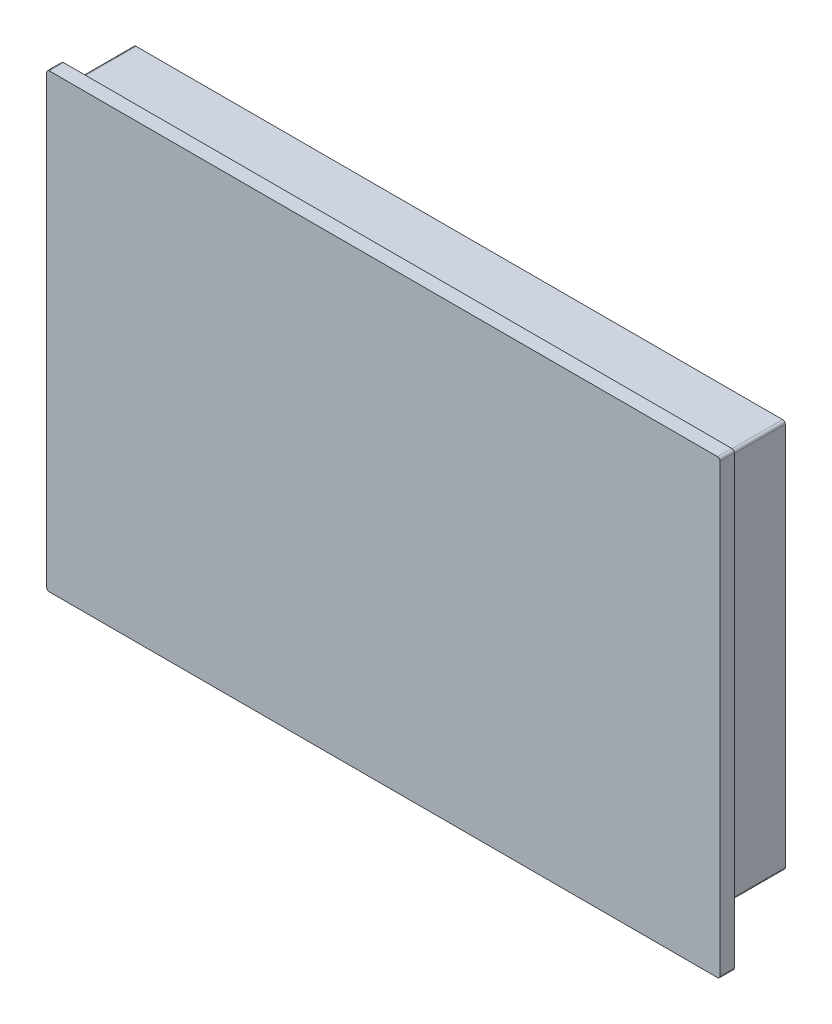
SolidWorks part; units mm, degrees
ref_plane "Front Plane" through (0, 0, 0) normal (0, 0, 1) x (1, 0, 0)
ref_plane "Top Plane" through (0, 0, 0) normal (0, 1, 0) x (1, 0, 0)
ref_plane "Right Plane" through (0, 0, 0) normal (1, 0, 0) x (0, 0, -1)
sketch "Sketch1" plane through (0, 0, 0) normal (0, 0, 1) x (1, 0, 0)
  line L1 (-63.8, 42.75) -> (63.8, 42.75)
  line L2 (-63.8, 42.75) -> (-63.8, -42.75)
  line L3 (-63.8, -42.75) -> (63.8, -42.75)
  line L4 (63.8, 42.75) -> (63.8, -42.75)
  line L5 (-63.8, 42.75) -> (63.8, -42.75) construction
  line L6 (-63.8, -42.75) -> (63.8, 42.75) construction
  point P0 (0, 0)
  dimension "D1" = 127.6
  dimension "D2" = 85.5
extrude "Boss-Extrude1" add sketch "Sketch1" along normal blind 14.4
sketch "Sketch2" plane through (0, 0, 0) normal (0, 0, -1) x (-1, 0, 0)
  line L1 (-61.75, 40.6) -> (61.75, 40.6)
  line L2 (-61.75, 40.6) -> (-61.75, -40.6)
  line L3 (-61.75, -40.6) -> (61.75, -40.6)
  line L4 (61.75, 40.6) -> (61.75, -40.6)
  line L5 (-61.75, 40.6) -> (61.75, -40.6) construction
  line L6 (-61.75, -40.6) -> (61.75, 40.6) construction
  line L16 (-63.8, 42.75) -> (-63.8, -42.75)
  line L17 (-63.8, -42.75) -> (63.8, -42.75)
  line L18 (63.8, -42.75) -> (63.8, 42.75)
  line L19 (63.8, 42.75) -> (-63.8, 42.75)
  line L20 (-63.8, 42.75) -> (-63.8, -42.75)
  line L21 (-63.8, -42.75) -> (63.8, -42.75)
  line L22 (63.8, -42.75) -> (63.8, 42.75)
  line L23 (63.8, 42.75) -> (-63.8, 42.75)
  point P2 (0, 0)
  dimension "D1" = 123.5
  dimension "D3" = 81.2
  dimension "D2" = 0
extrude "Cut-Extrude1" cut sketch "Sketch2" against normal blind 11.7
fillet "Fillet1" radius 0.5 8 edges at (63.8, 42.75, 13.05) (63.8, -42.75, 13.05) (-63.8, -42.75, 13.05) (-63.8, 42.75, 13.05) (-61.75, 40.6, 5.85) (-61.75, -40.6, 5.85) (61.75, -40.6, 5.85) (61.75, 40.6, 5.85)
sketch "Sketch3" plane through (0, 0, 0) normal (0, 0, -1) x (-1, 0, 0)
  line L2 (-63.8, 42.25) -> (-63.8, -42.25) construction
  line L3 (63.3, 42.75) -> (-63.3, 42.75) construction
  circle A0 centre (-49.4, 31.35) radius 3.4
  dimension "D1" = 14.4
  dimension "D3" = 6.8
  dimension "D2" = 11.4
extrude "Cut-Extrude2" cut sketch "Sketch3" against normal blind 9.8
pattern_linear "LPattern2" count 8 spacing 9 along (0, -1, 0) count 12 spacing 9 along (-1, 0, 0) of "Cut-Extrude2"
sketch "Sketch4" plane through (0, 0, 0) normal (0, 0, -1) x (-1, 0, 0)
  line L0 (-64.3379, -30.2508) -> (-51.8058, -42.7829)
  line L1 (-51.8058, -42.7829) -> (-64.3379, -42.7829)
  line L2 (-64.3379, -42.7829) -> (-64.3379, -30.2508)
  line L3 (0, 52.626) -> (0, -59.7099) construction
  line L4 (64.3379, -42.7829) -> (64.3379, -30.2508)
  line L5 (51.8058, -42.7829) -> (64.3379, -42.7829)
  line L6 (64.3379, -30.2508) -> (51.8058, -42.7829)
  dimension "D1" = 45
extrude "Cut-Extrude3" cut sketch "Sketch4" against normal blind 11.7
fillet "Fillet2" radius 0.5 4 edges at (-61.75, -32.8387, 5.85) (-53.9887, -40.6, 5.85) (53.9887, -40.6, 5.85) (61.75, -32.8387, 5.85)
